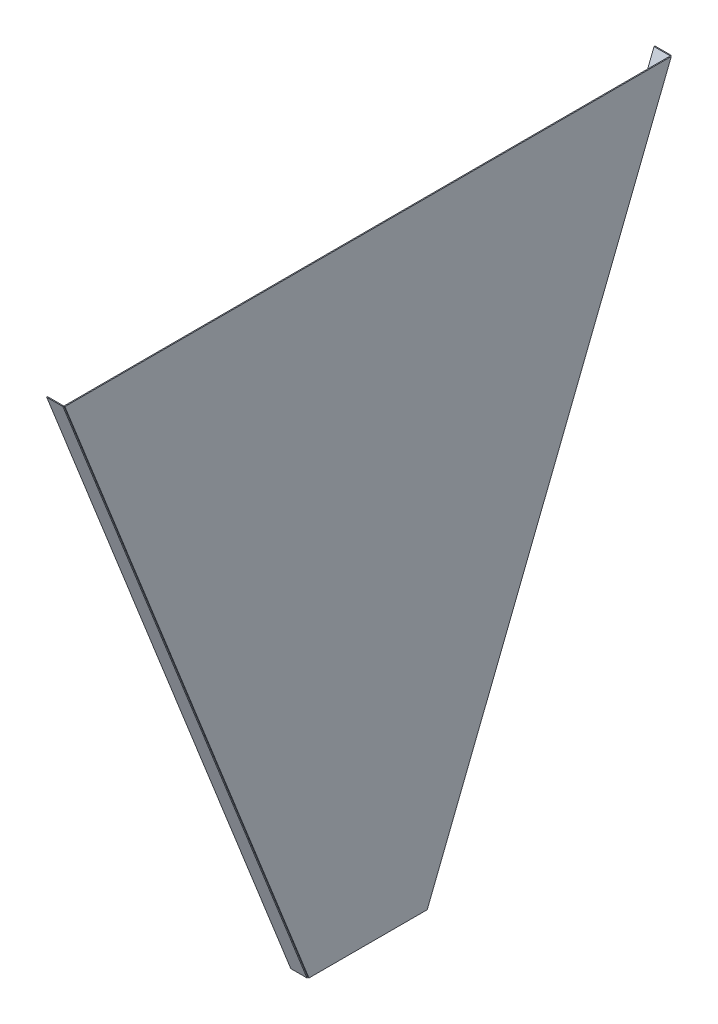
SolidWorks part; units mm, degrees
ref_plane "Front Plane" through (0, 0, 0) normal (0, 0, 1) x (1, 0, 0)
ref_plane "Top Plane" through (0, 0, 0) normal (0, 1, 0) x (1, 0, 0)
ref_plane "Right Plane" through (0, 0, 0) normal (1, 0, 0) x (0, 0, -1)
sketch "Sketch1" plane through (0, 0, 0) normal (1, 0, 0) x (0, 0, -1)
  line L0 (0, 0) -> (374.5, 0) construction
  line L1 (0, 0) -> (-374.5, 0) construction
  line L2 (-374.5, 0) -> (-374.5, 381) construction
  line L3 (374.5, 0) -> (374.5, 381) construction
  line L4 (-374.5, 381) -> (374.5, 381)
  line L5 (0, 0) -> (0, -381) construction
  line L6 (0, -381) -> (-73, -381)
  line L7 (0, -381) -> (73, -381)
  line L8 (374.5, 381) -> (73, -381)
  line L9 (-374.5, 381) -> (-73, -381)
  dimension "D1" = 374.5
  dimension "D2" = 381
  dimension "D3" = 381
  dimension "D4" = 73
  dimension "D5" = 819.4793
extrude "Boss-Extrude1" add sketch "Sketch1" along normal blind 1.22
sketch "Sketch3" plane through (0, 0, 0) normal (-1, 0, 0) x (0, 0, 1)
  line L0 (73, -381) -> (74.2, -381)
  line L1 (74.2, -381) -> (375.7, 381)
  line L2 (375.7, 381) -> (374.5, 381)
  line L3 (0, -381) -> (0, 381) construction
  line L4 (73, -381) -> (-73, -381) construction
  line L5 (-374.5, 381) -> (374.5, 381) construction
  line L6 (-73, -381) -> (-74.2, -381)
  line L7 (-375.7, 381) -> (-374.5, 381)
  line L8 (-74.2, -381) -> (-375.7, 381)
  line L11 (374.5, 381) -> (73, -381)
  line L12 (-374.5, 381) -> (-73, -381)
  dimension "D1" = 1.2
extrude "Boss-Extrude2" add sketch "Sketch3" along normal blind 20 separate body contours L1 L2 L11 L0 | L12 L6 L8 L7
